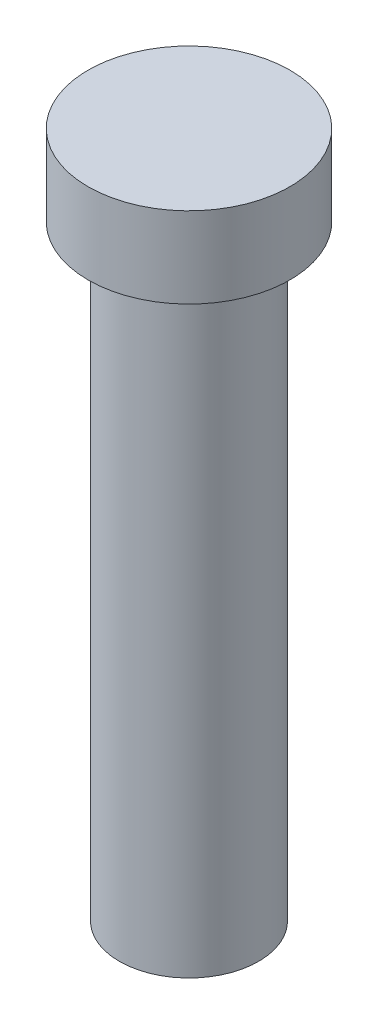
SolidWorks part; units mm, degrees
ref_plane "Front Plane" through (0, 0, 0) normal (0, 0, 1) x (1, 0, 0)
ref_plane "Top Plane" through (0, 0, 0) normal (0, 1, 0) x (1, 0, 0)
ref_plane "Right Plane" through (0, 0, 0) normal (1, 0, 0) x (0, 0, -1)
sketch "Sketch1" plane through (0, 0, 0) normal (0, 1, 0) x (1, 0, 0)
  circle A0 centre (0, 0) radius 3.45
  dimension "6.9" = 6.9
extrude "Boss-Extrude1" add sketch "Sketch1" along normal blind 30
sketch "Sketch2" plane through (0, 30, 0) normal (0, 1, 0) x (1, 0, 0)
  circle A0 centre (0, 0) radius 5
  dimension "10" = 10
extrude "Boss-Extrude2" add sketch "Sketch2" along normal blind 4
